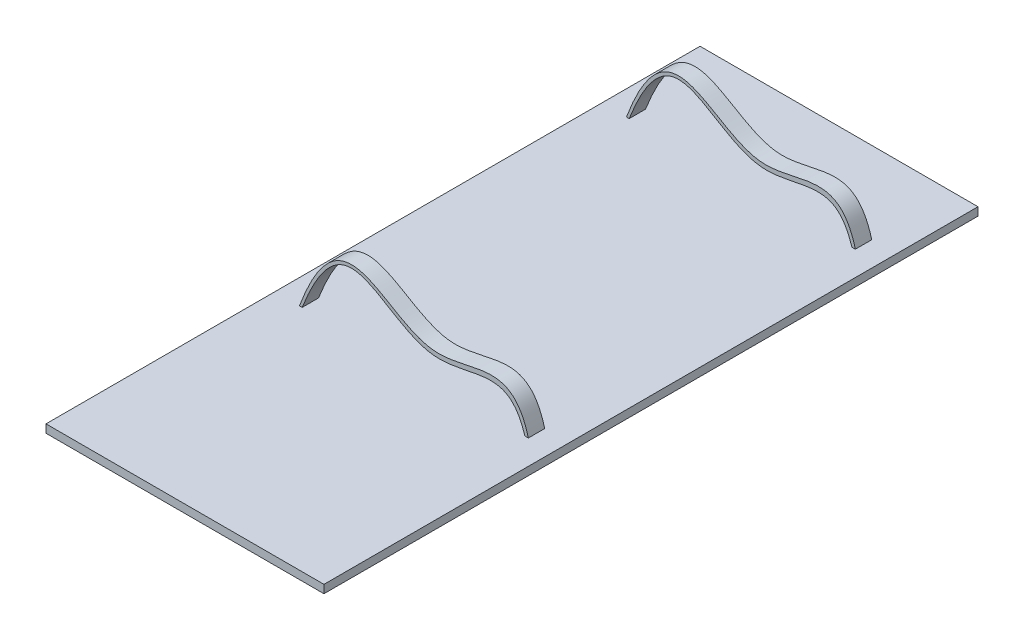
SolidWorks part; units mm, degrees
ref_plane "Front" through (0, 0, 0) normal (0, 0, 1) x (1, 0, 0)
ref_plane "Top" through (0, 0, 0) normal (0, 1, 0) x (1, 0, 0)
ref_plane "Right" through (0, 0, 0) normal (1, 0, 0) x (0, 0, -1)
sketch "Sketch1" plane through (0, 0, 0) normal (0, 1, 0) x (1, 0, 0)
  line L1 (0, 0) -> (85, 0)
  line L2 (0, 0) -> (0, 200)
  line L3 (0, 200) -> (85, 200)
  line L4 (85, 0) -> (85, 200)
  dimension "D1" = 200
  dimension "D2" = 85
extrude "Boss-Extrude1" add sketch "Sketch1" along normal blind 2.5
ref_plane "Plane1" through (0, 0, -175) normal (0, 0, -1) x (-1, 0, 0)
sketch "Sketch3" plane through (0, 0, -175) normal (0, 0, -1) x (-1, 0, 0)
  line L0 (0, 2.5) -> (-85, 2.5) construction
  line L1 (-77.5, 2.5) -> (-76.4501, 2.5)
  line L2 (-8.3367, 2.5) -> (-7.5, 2.5)
  line L3 (-85, 2.5) -> (0, 2.5) construction
  line L4 (-85, 2.5) -> (0, 2.5) construction
  line L5 (-42.5, 2.5) -> (-42.5, 15.4149) construction
  spline S0 degree 3 poles (-77.5, 2.5) (-72.4584, 21.0919) (-41.3863, -5.2633) (-20.7504, 38.155) (-7.5, 2.5) knots 0 0 0 0 0.411408 1 1 1 1
  spline S1 degree 3 poles (-76.4501, 2.5) (-76.352, 2.8132) (-76.1417, 3.4488) (-75.7129, 4.6064) (-75.1417, 5.9149) (-74.4126, 7.2552) (-73.3875, 8.764) (-72.0225, 10.1662) (-70.2637, 11.2326) (-68.3484, 11.8199) (-65.5524, 12.0796) (-61.6408, 11.6006) (-56.5471, 10.4791) (-52.1541, 9.7942) (-48.6101, 9.8536) (-45.1382, 10.485) (-41.0552, 12.1137) (-36.4556, 14.7462) (-32.0984, 17.4435) (-27.955, 19.606) (-24.0674, 20.6515) (-21.0365, 20.2607) (-18.5405, 18.9238) (-16.6037, 17.2893) (-14.6064, 14.926) (-12.9007, 12.2801) (-11.515, 9.72) (-10.4662, 7.5709) (-9.5824, 5.5763) (-8.8743, 3.8659) (-8.512, 2.9517) (-8.3367, 2.5) knots 0 0 0 0 0.007812 0.015625 0.03125 0.046875 0.0625 0.09375 0.125 0.15625 0.1875 0.25 0.3125 0.375 0.40625 0.4375 0.5 0.5625 0.625 0.6875 0.75 0.8125 0.84375 0.875 0.90625 0.9375 0.953125 0.96875 0.984375 0.992188 1 1 1 1
  dimension "D1" = 70
  dimension "D2" = 7.5
extrude "Boss-Extrude3" add sketch "Sketch3" against normal blind 5
pattern_linear "LPattern1" count 2 spacing 100 along (0, 0, 1) of "Boss-Extrude3"
